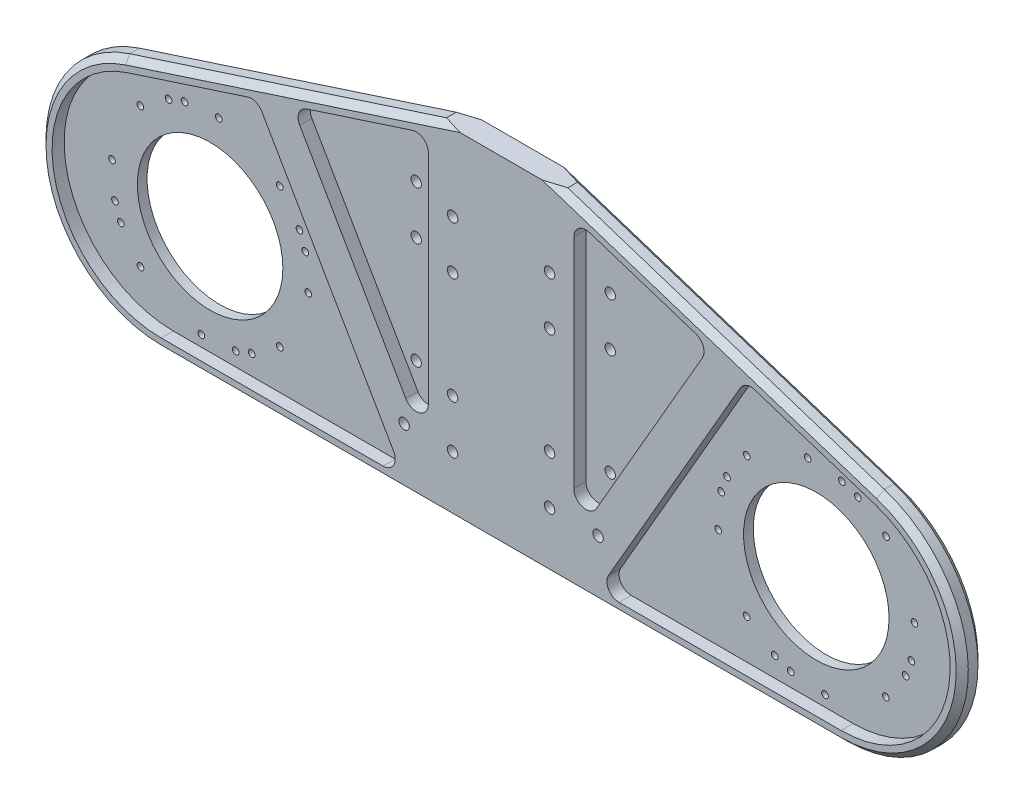
SolidWorks part; units mm, degrees
material "6061 合金"
ref_plane "前视基准面" through (0, 0, 0) normal (0, 0, 1) x (1, 0, 0)
ref_plane "上视基准面" through (0, 0, 0) normal (0, 1, 0) x (1, 0, 0)
ref_plane "右视基准面" through (0, 0, 0) normal (1, 0, 0) x (0, 0, -1)
other "Configuration Table"
sketch "草图1" plane through (0, 0, 0) normal (0, 0, 1) x (1, 0, 0)
  line L0 (0, 0) -> (0, 280) construction
  line L1 (0, 280) -> (861.7514, 0)
  line L3 (861.7514, 0) -> (0, 0)
  line L4 (-50, 352.899) -> (-50, -139.8009) construction
  line L5 (-961.7514, 0) -> (-100, 0)
  line L6 (-100, 280) -> (-961.7514, 0)
  line L7 (-100, 0) -> (-100, 280) construction
  line L8 (-100, 280) -> (0, 280)
  line L9 (0, 0) -> (-100, 0)
  circle A0 centre (200, 100) radius 85 construction
  circle A1 centre (200, 100) radius 60
  circle A2 centre (-300, 100) radius 85 construction
  circle A3 centre (-300, 100) radius 60
  dimension "D1" = 170
  dimension "D4" = 120
  dimension "D2" = 200
  dimension "D3" = 72
  dimension "D5" = 280
  dimension "D6" = 100
  dimension "D7" = 50
extrude "凸台-拉伸1" add sketch "草图1" along normal blind 8 contours L9 L3 L1 L8 L6 L5 A1 A3
fillet "圆角1" radius 100 2 edges at (861.7514, 0, 4) (-961.7514, 0, 4)
sketch "草图2" plane through (0, 0, 8) normal (0, 0, 1) x (1, 0, 0)
  line L0 (10, 266.2362) -> (10, 35.359)
  line L1 (30, 10) -> (230.3762, 10)
  line L2 (10, 266.2362) -> (122.2414, 229.7667)
  line L9 (10, 35.359) -> (122.2414, 229.7667)
  line L10 (30, 10) -> (151.4105, 220.2891)
  line L11 (151.4105, 220.2891) -> (258.1878, 185.5951)
  line L12 (10, 35.359) -> (10, 10) construction
  line L13 (10, 10) -> (30, 10) construction
  line L15 (0, 280) -> (261.2779, 195.1057) construction
  line L16 (230.3762, 0) -> (-330.3762, 0) construction
  line L19 (0, 280) -> (261.2779, 195.1057)
  line L24 (-50, 336.5114) -> (-50, -134.6936) construction
  line L29 (-100, 280) -> (0, 280) construction
  line L30 (230.3762, 0) -> (-330.3762, 0)
  line L31 (0, 280) -> (-100, 280)
  line L39 (-50, 280) -> (-50, 0)
  line L40 (-110, 10) -> (-130, 10) construction
  line L41 (-110, 35.359) -> (-110, 10) construction
  line L42 (-100, 280) -> (-361.2779, 195.1057)
  line L43 (-251.4105, 220.2891) -> (-358.1878, 185.5951)
  line L44 (-130, 10) -> (-251.4105, 220.2891)
  line L45 (-110, 35.359) -> (-222.2414, 229.7667)
  line L46 (-110, 266.2362) -> (-222.2414, 229.7667)
  line L47 (-130, 10) -> (-330.3762, 10)
  line L48 (-110, 266.2362) -> (-110, 35.359)
  arc A0 (230.3762, 10) -> (258.1878, 185.5951) centre (230.3762, 100) ccw
  arc A5 (230.3762, 0) -> (261.2779, 195.1057) centre (230.3762, 100) ccw construction
  arc A7 (230.3762, 0) -> (261.2779, 195.1057) centre (230.3762, 100) ccw
  arc A12 (-330.3762, 0) -> (-361.2779, 195.1057) centre (-330.3762, 100) cw
  arc A13 (-330.3762, 10) -> (-358.1878, 185.5951) centre (-330.3762, 100) cw
  point P33 (-50, 280)
  point P34 (-50, 0)
  line M64 (-100, 280) -> (-361.2779, 195.1057)
  arc M65 (-361.2779, 195.1057) -> (-330.3762, 0) centre (-330.3762, 100) ccw
  line M66 (-330.3762, 0) -> (230.3762, 0)
  arc M67 (230.3762, 0) -> (261.2779, 195.1057) centre (230.3762, 100) ccw
  line M68 (261.2779, 195.1057) -> (0, 280)
  line M69 (0, 280) -> (-100, 280)
  dimension "D4" = 10
  dimension "D2" = 10
  dimension "D3" = 10
  dimension "D6" = 30
  dimension "D7" = 60
  dimension "D8" = 20
  dimension "D1" = 10
extrude "凸台-拉伸2" add sketch "草图2" along normal blind 10 contours L39 L31 L46 L48 L45 L47 A13 L43 L44 M64 M65 M66 | L39 L30 A0 L1 L10 L11 L9 L0 L2 M69 M67 M68
fillet "圆角2" radius 10 10 edges at (10, 35.359, 13) (30, 10, 13) (122.2414, 229.7667, 13) (151.4105, 220.2891, 13) (10, 266.2362, 13) (-130, 10, 13) (-251.4105, 220.2891, 13) (-110, 266.2362, 13) (-222.2414, 229.7667, 13) (-110, 35.359, 13)
chamfer "倒角1" distance 5 angle 45 10 edges at (130.639, 237.5528, 0) (-50, 0, 0) (329.1451, 84.3566, 0) (-429.1451, 84.3566, 0) (-50, 0, 18) (329.1451, 84.3566, 18) (130.639, 237.5528, 18) (-230.639, 237.5528, 18) (-429.1451, 84.3566, 18) (-230.639, 237.5528, 0)
sketch "草图3" plane through (0, 0, 0) normal (0, 0, -1) x (-1, 0, 0)
  line L0 (144, 30) -> (100, 30) construction
  line L1 (-44, 236) -> (34, 236) construction
  line L2 (-44, 236) -> (-44, 158) construction
  line L3 (-44, 158) -> (34, 158) construction
  line L5 (-44, 108) -> (34, 108) construction
  line L6 (-44, 108) -> (-44, 30) construction
  line L7 (-44, 30) -> (0, 30) construction
  line L9 (144, 108) -> (144, 30) construction
  line L10 (330.3762, 0) -> (-230.3762, 0) construction
  line L11 (50, 335.2852) -> (50, -119.0767) construction
  line L12 (144, 108) -> (66, 108) construction
  line L13 (144, 158) -> (66, 158) construction
  line L14 (144, 236) -> (144, 158) construction
  line L15 (144, 236) -> (66, 236) construction
  circle A0 centre (-30, 217) radius 4.3
  circle A1 centre (-30, 177) radius 4.3
  circle A2 centre (10, 217) radius 4.3
  circle A3 centre (10, 177) radius 4.3
  circle A4 centre (-30, 89) radius 4.3
  circle A5 centre (10, 89) radius 4.3
  circle A6 centre (-30, 49) radius 4.3
  circle A7 centre (10, 49) radius 4.3
  circle A8 centre (300, 100) radius 60 construction
  circle A9 centre (-200, 100) radius 60 construction
  circle A10 centre (90, 49) radius 4.3
  circle A11 centre (130, 49) radius 4.3
  circle A12 centre (90, 89) radius 4.3
  circle A13 centre (130, 89) radius 4.3
  circle A14 centre (90, 177) radius 4.3
  circle A15 centre (90, 217) radius 4.3
  circle A16 centre (130, 177) radius 4.3
  circle A17 centre (130, 217) radius 4.3
  dimension "D7" = 8.6
  dimension "D16" = 8.6
  dimension "D1" = 78
  dimension "D2" = 78
  dimension "D3" = 54
  dimension "D4" = 78
  dimension "D5" = 30
  dimension "D6" = 50
  dimension "D8" = 19
  dimension "D9" = 19
  dimension "D10" = 19
  dimension "D11" = 19
  dimension "D12" = 14
  dimension "D13" = 14
  dimension "D14" = 40
  dimension "D17" = 19
  dimension "D18" = 19
  dimension "D19" = 19
  dimension "D20" = 19
  dimension "D21" = 14
  dimension "D22" = 14
extrude "切除-拉伸1" cut sketch "草图3" against normal through all both
sketch "草图4" plane through (0, 0, 8) normal (0, 0, 1) x (1, 0, 0)
  line L0 (-50, 330.4726) -> (-50, -61.6586) construction
  arc A0 (259.7806, 158.4465) -> (255.249, 156.3335) centre (257.5148, 157.39) ccw construction
  arc A1 (278.6673, 106.1128) -> (283.1989, 108.2258) centre (280.9331, 107.1693) ccw construction
  arc A2 (276.1928, 77.8292) -> (280.7244, 79.9423) centre (278.4586, 78.8857) ccw construction
  arc A3 (271.409, 64.6857) -> (275.9405, 66.7988) centre (273.6748, 65.7423) ccw construction
  arc A4 (255.1242, 41.4287) -> (259.6558, 43.5418) centre (257.39, 42.4852) ccw construction
  arc A5 (204.9035, 18.0104) -> (209.4351, 20.1235) centre (207.1693, 19.0669) ccw construction
  arc A6 (176.62, 20.4849) -> (181.1515, 22.598) centre (178.8857, 21.5414) ccw construction
  arc A7 (163.4765, 25.2687) -> (168.008, 27.3818) centre (165.7423, 26.3252) ccw construction
  arc A8 (140.2194, 41.5535) -> (144.751, 43.6665) centre (142.4852, 42.61) ccw construction
  arc A9 (121.3327, 93.8872) -> (116.8011, 91.7742) centre (119.0669, 92.8307) ccw construction
  arc A10 (123.8072, 122.1708) -> (119.2756, 120.0577) centre (121.5414, 121.1143) ccw construction
  arc A11 (128.591, 135.3143) -> (124.0595, 133.2012) centre (126.3252, 134.2577) ccw construction
  arc A12 (144.8758, 158.5713) -> (140.3442, 156.4582) centre (142.61, 157.5148) ccw construction
  arc A13 (195.0965, 181.9896) -> (190.5649, 179.8765) centre (192.8307, 180.9331) ccw construction
  arc A14 (223.38, 179.5151) -> (218.8485, 177.402) centre (221.1143, 178.4586) ccw construction
  arc A15 (236.5235, 174.7313) -> (231.992, 172.6182) centre (234.2577, 173.6748) ccw construction
  arc A16 (259.7806, 158.4465) -> (255.249, 156.3335) centre (257.5148, 157.39) ccw construction
  arc A17 (278.6673, 106.1128) -> (283.1989, 108.2258) centre (280.9331, 107.1693) ccw construction
  arc A18 (276.1928, 77.8292) -> (280.7244, 79.9423) centre (278.4586, 78.8857) ccw construction
  arc A19 (271.409, 64.6857) -> (275.9405, 66.7988) centre (273.6748, 65.7423) ccw construction
  arc A20 (255.1242, 41.4287) -> (259.6558, 43.5418) centre (257.39, 42.4852) ccw construction
  arc A21 (204.9035, 18.0104) -> (209.4351, 20.1235) centre (207.1693, 19.0669) ccw construction
  arc A22 (176.62, 20.4849) -> (181.1515, 22.598) centre (178.8857, 21.5414) ccw construction
  arc A23 (163.4765, 25.2687) -> (168.008, 27.3818) centre (165.7423, 26.3252) ccw construction
  arc A24 (140.2194, 41.5535) -> (144.751, 43.6665) centre (142.4852, 42.61) ccw construction
  arc A25 (121.3327, 93.8872) -> (116.8011, 91.7742) centre (119.0669, 92.8307) ccw construction
  arc A26 (123.8072, 122.1708) -> (119.2756, 120.0577) centre (121.5414, 121.1143) ccw construction
  arc A27 (128.591, 135.3143) -> (124.0595, 133.2012) centre (126.3252, 134.2577) ccw construction
  arc A28 (144.8758, 158.5713) -> (140.3442, 156.4582) centre (142.61, 157.5148) ccw construction
  arc A29 (195.0965, 181.9896) -> (190.5649, 179.8765) centre (192.8307, 180.9331) ccw construction
  arc A30 (223.38, 179.5151) -> (218.8485, 177.402) centre (221.1143, 178.4586) ccw construction
  arc A31 (236.5235, 174.7313) -> (231.992, 172.6182) centre (234.2577, 173.6748) ccw construction
  circle A32 centre (257.5148, 157.39) radius 2.75
  circle A33 centre (234.2577, 173.6748) radius 2.75
  circle A34 centre (221.1143, 178.4586) radius 2.75
  circle A35 centre (192.8307, 180.9331) radius 2.75
  circle A36 centre (142.61, 157.5148) radius 2.75
  circle A37 centre (126.3252, 134.2577) radius 2.75
  circle A38 centre (121.5414, 121.1143) radius 2.75
  circle A39 centre (119.0669, 92.8307) radius 2.75
  circle A40 centre (142.4852, 42.61) radius 2.75
  circle A41 centre (165.7423, 26.3252) radius 2.75
  circle A42 centre (178.8857, 21.5414) radius 2.75
  circle A43 centre (207.1693, 19.0669) radius 2.75
  circle A44 centre (257.39, 42.4852) radius 2.75
  circle A45 centre (273.6748, 65.7423) radius 2.75
  circle A46 centre (278.4586, 78.8857) radius 2.75
  circle A47 centre (280.9331, 107.1693) radius 2.75
  circle A48 centre (200, 100) radius 60 construction
  circle A49 centre (-300, 100) radius 60 construction
  arc A50 (-336.5235, 174.7313) -> (-331.992, 172.6182) centre (-334.2577, 173.6748) cw construction
  arc A51 (-323.38, 179.5151) -> (-318.8485, 177.402) centre (-321.1143, 178.4586) cw construction
  arc A52 (-295.0965, 181.9896) -> (-290.5649, 179.8765) centre (-292.8307, 180.9331) cw construction
  arc A53 (-244.8758, 158.5713) -> (-240.3442, 156.4582) centre (-242.61, 157.5148) cw construction
  arc A54 (-228.591, 135.3143) -> (-224.0595, 133.2012) centre (-226.3252, 134.2577) cw construction
  arc A55 (-223.8072, 122.1708) -> (-219.2756, 120.0577) centre (-221.5414, 121.1143) cw construction
  arc A56 (-221.3327, 93.8872) -> (-216.8011, 91.7742) centre (-219.0669, 92.8307) cw construction
  arc A57 (-240.2194, 41.5535) -> (-244.751, 43.6665) centre (-242.4852, 42.61) cw construction
  arc A58 (-263.4765, 25.2687) -> (-268.008, 27.3818) centre (-265.7423, 26.3252) cw construction
  arc A59 (-276.62, 20.4849) -> (-281.1515, 22.598) centre (-278.8857, 21.5414) cw construction
  arc A60 (-304.9035, 18.0104) -> (-309.4351, 20.1235) centre (-307.1693, 19.0669) cw construction
  arc A61 (-355.1242, 41.4287) -> (-359.6558, 43.5418) centre (-357.39, 42.4852) cw construction
  arc A62 (-371.409, 64.6857) -> (-375.9405, 66.7988) centre (-373.6748, 65.7423) cw construction
  arc A63 (-376.1928, 77.8292) -> (-380.7244, 79.9423) centre (-378.4586, 78.8857) cw construction
  arc A64 (-378.6673, 106.1128) -> (-383.1989, 108.2258) centre (-380.9331, 107.1693) cw construction
  arc A65 (-359.7806, 158.4465) -> (-355.249, 156.3335) centre (-357.5148, 157.39) cw construction
  circle A66 centre (-380.9331, 107.1693) radius 2.75
  circle A67 centre (-378.4586, 78.8857) radius 2.75
  circle A68 centre (-373.6748, 65.7423) radius 2.75
  circle A69 centre (-357.39, 42.4852) radius 2.75
  circle A70 centre (-307.1693, 19.0669) radius 2.75
  circle A71 centre (-278.8857, 21.5414) radius 2.75
  circle A72 centre (-265.7423, 26.3252) radius 2.75
  circle A73 centre (-242.4852, 42.61) radius 2.75
  circle A74 centre (-219.0669, 92.8307) radius 2.75
  circle A75 centre (-221.5414, 121.1143) radius 2.75
  circle A76 centre (-226.3252, 134.2577) radius 2.75
  circle A77 centre (-242.61, 157.5148) radius 2.75
  circle A78 centre (-292.8307, 180.9331) radius 2.75
  circle A79 centre (-321.1143, 178.4586) radius 2.75
  circle A80 centre (-334.2577, 173.6748) radius 2.75
  circle A81 centre (-357.5148, 157.39) radius 2.75
  dimension "D1" = 5.5
extrude "切除-拉伸2" cut sketch "草图4" against normal blind 10 contours A44 | A45 | A46 | A47 | A32 | A33 | A34 | A35 | A36 | A37 | A38 | A39 | A40 | A41 | A42 | A73 | A72 | A71 | A70 | A69 | A68 | A67 | A66 | A81 | A80 | A79 | A78 | A77 | A76 | A75 | A74 | A43
sketch "草图5" plane through (0, 0, 0) normal (0, 0, -1) x (-1, 0, 0)
  line L0 (50, 354.5789) -> (50, -118.9875) construction
  circle A0 centre (-192.8307, 180.9331) radius 6
  circle A1 centre (-142.61, 157.5148) radius 6
  circle A2 centre (-126.3252, 134.2577) radius 6
  circle A3 centre (-121.5414, 121.1143) radius 6
  circle A4 centre (-119.0669, 92.8307) radius 6
  circle A5 centre (-142.4852, 42.61) radius 6
  circle A6 centre (-165.7423, 26.3252) radius 6
  circle A7 centre (-178.8857, 21.5414) radius 6
  circle A8 centre (-207.1693, 19.0669) radius 6
  circle A9 centre (-257.39, 42.4852) radius 6
  circle A10 centre (-273.6748, 65.7423) radius 6
  circle A11 centre (-278.4586, 78.8857) radius 6
  circle A12 centre (-280.9331, 107.1693) radius 6
  circle A13 centre (-257.5148, 157.39) radius 6
  circle A14 centre (-234.2577, 173.6748) radius 6
  circle A15 centre (-221.1143, 178.4586) radius 6
  circle A16 centre (300, 100) radius 60 construction
  circle A17 centre (-200, 100) radius 60 construction
  circle A18 centre (321.1143, 178.4586) radius 6
  circle A19 centre (334.2577, 173.6748) radius 6
  circle A20 centre (357.5148, 157.39) radius 6
  circle A21 centre (380.9331, 107.1693) radius 6
  circle A22 centre (378.4586, 78.8857) radius 6
  circle A23 centre (373.6748, 65.7423) radius 6
  circle A24 centre (357.39, 42.4852) radius 6
  circle A25 centre (307.1693, 19.0669) radius 6
  circle A26 centre (278.8857, 21.5414) radius 6
  circle A27 centre (265.7423, 26.3252) radius 6
  circle A28 centre (242.4852, 42.61) radius 6
  circle A29 centre (219.0669, 92.8307) radius 6
  circle A30 centre (221.5414, 121.1143) radius 6
  circle A31 centre (226.3252, 134.2577) radius 6
  circle A32 centre (242.61, 157.5148) radius 6
  circle A33 centre (292.8307, 180.9331) radius 6
  dimension "D1" = 12
extrude "切除-拉伸3" cut sketch "草图5" against normal blind 4
